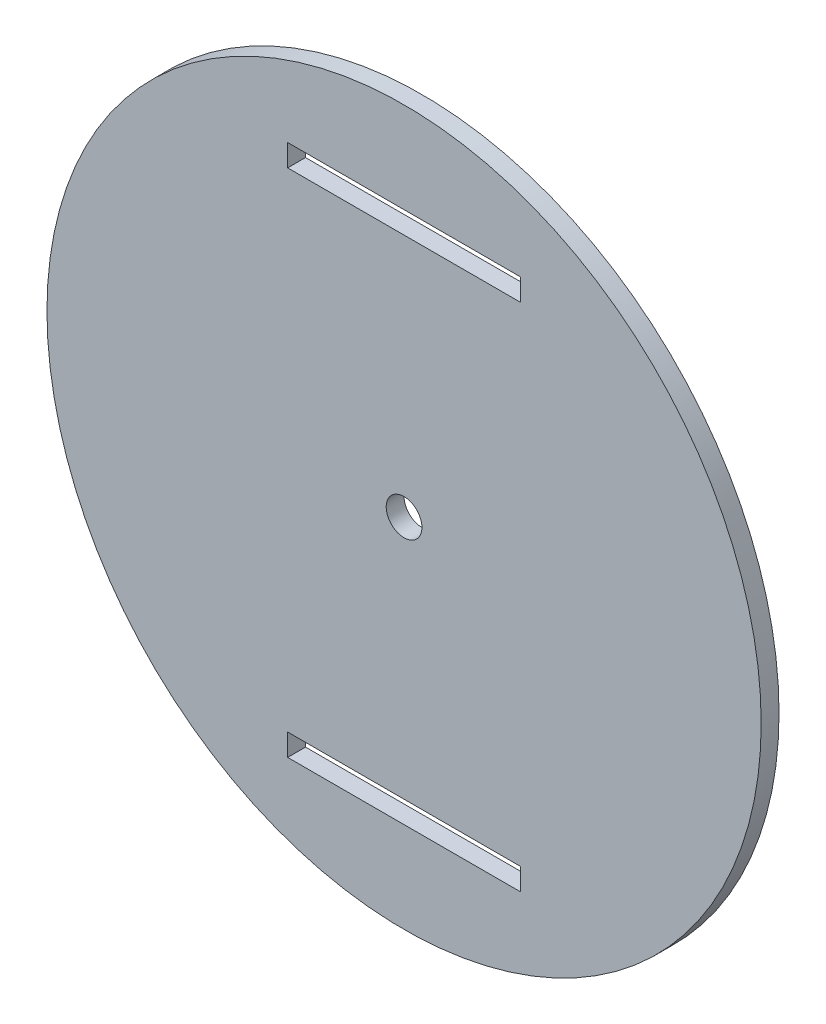
SolidWorks part; units mm, degrees
ref_plane "Front Plane" through (0, 0, 0) normal (0, 0, 1) x (1, 0, 0)
ref_plane "Top Plane" through (0, 0, 0) normal (0, 1, 0) x (1, 0, 0)
ref_plane "Right Plane" through (0, 0, 0) normal (1, 0, 0) x (0, 0, -1)
sketch "Sketch1" plane through (0, 0, 0) normal (0, 0, 1) x (1, 0, 0)
  circle A0 centre (0, 0) radius 20
extrude "Boss-Extrude1" add sketch "Sketch1" along normal blind 1
sketch "Sketch2" plane through (0, 0, 1) normal (0, 0, 1) x (1, 0, 0)
  line L0 (0, 0) -> (8.9807, 0) construction
  line L1 (8.9807, 0) -> (0, 0) construction
  line L2 (0, 0) -> (0, 5.6234) construction
  line L3 (-6.5187, -13.6808) -> (6.5187, -13.6808)
  line L4 (-6.5187, 14.9118) -> (6.5187, 14.9118)
  line L5 (-6.5187, 14.9118) -> (-6.5187, 13.6808)
  line L6 (-6.5187, 13.6808) -> (6.5187, 13.6808)
  line L7 (6.5187, 14.9118) -> (6.5187, 13.6808)
  line L8 (-6.5187, 14.9118) -> (6.5187, 13.6808) construction
  line L9 (-6.5187, 13.6808) -> (6.5187, 14.9118) construction
  line L10 (6.5187, -14.9118) -> (6.5187, -13.6808)
  line L11 (-6.5187, -14.9118) -> (6.5187, -14.9118)
  line L12 (-6.5187, -14.9118) -> (-6.5187, -13.6808)
  line L13 (-6.5187, -13.6808) -> (6.5187, -14.9118) construction
  line L14 (-6.5187, -14.9118) -> (6.5187, -13.6808) construction
  point P4 (0, 14.2963)
  point P13 (0, -14.2963)
extrude "Cut-Extrude1" cut sketch "Sketch2" against normal blind 1
sketch "Sketch3" plane through (0, 0, 1) normal (0, 0, 1) x (1, 0, 0)
  circle A0 centre (0, 0) radius 1
extrude "Cut-Extrude2" cut sketch "Sketch3" against normal blind 1
